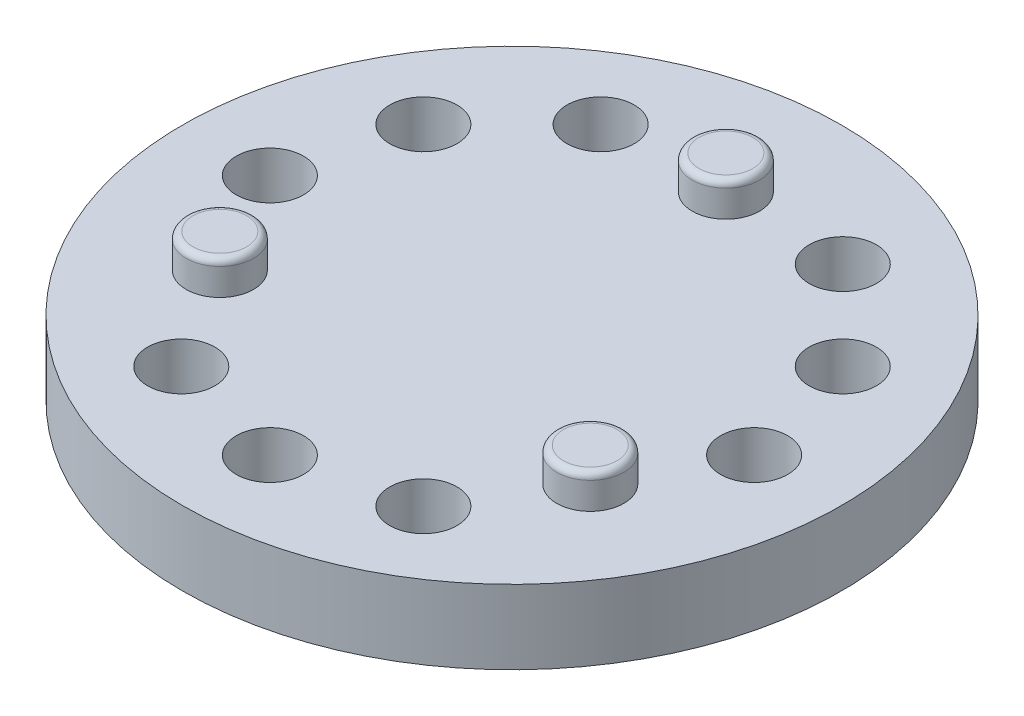
SolidWorks part; units mm, degrees
ref_plane "Front Plane" through (0, 0, 0) normal (0, 0, 1) x (1, 0, 0)
ref_plane "Top Plane" through (0, 0, 0) normal (0, 1, 0) x (1, 0, 0)
ref_plane "Right Plane" through (0, 0, 0) normal (1, 0, 0) x (0, 0, -1)
sketch "Sketch1" plane through (0, 0, 0) normal (0, 1, 0) x (1, 0, 0)
  circle A0 centre (0, 0) radius 24.5
extrude "Boss-Extrude1" add sketch "Sketch1" along normal blind 5.5
sketch "Sketch2" plane through (0, 5.5, 0) normal (0, 1, 0) x (1, 0, 0)
  circle A0 centre (0, 0) radius 18 construction
  circle A1 centre (0, 0) radius 15.9 construction
  circle A2 centre (0, 15.9) radius 2.5
  arc A3 (0, 18) -> (9, 15.5885) centre (0, 0) cw construction
  circle A4 centre (9, 15.5885) radius 2.5
  circle A5 centre (15.5885, 9) radius 2.5
  circle A6 centre (18, 0) radius 2.5
  circle A7 centre (13.7698, -7.95) radius 2.5
  circle A8 centre (-13.7383, -8.0044) radius 2.5
  circle A9 centre (9, -15.5885) radius 2.5
  circle A10 centre (0, -18) radius 2.5
  circle A11 centre (-9, -15.5885) radius 2.5
  circle A12 centre (-18, 0) radius 2.5
  circle A13 centre (-15.5885, 9) radius 2.5
  circle A14 centre (-9, 15.5885) radius 2.5
  point P15 (0, 0)
  point P20 (0, 0)
  point P34 (0, 0)
  dimension "D1" = 3
  dimension "D2" = 3
extrude "Cut-Extrude1" cut sketch "Sketch2" against normal blind 6.6 contours A11 | A13 | A12 | A10 | A9 | A14 | A4 | A5 | A6
sketch "Sketch6" plane through (0, 5.5, 0) normal (0, 1, 0) x (1, 0, 0)
  circle A0 centre (0, 0) radius 15.9 construction
  circle A1 centre (0, 15.9) radius 2.5
  circle A2 centre (13.7698, -7.95) radius 2.5
  circle A3 centre (-13.7698, -7.95) radius 2.5
  point P11 (0, 0)
extrude "Boss-Extrude2" add sketch "Sketch6" along normal blind 2.5
fillet "Fillet1" radius 0.5 3 edges at (13.7698, 8, 10.45) (0, 8, -13.4) (-13.7698, 8, 10.45)
